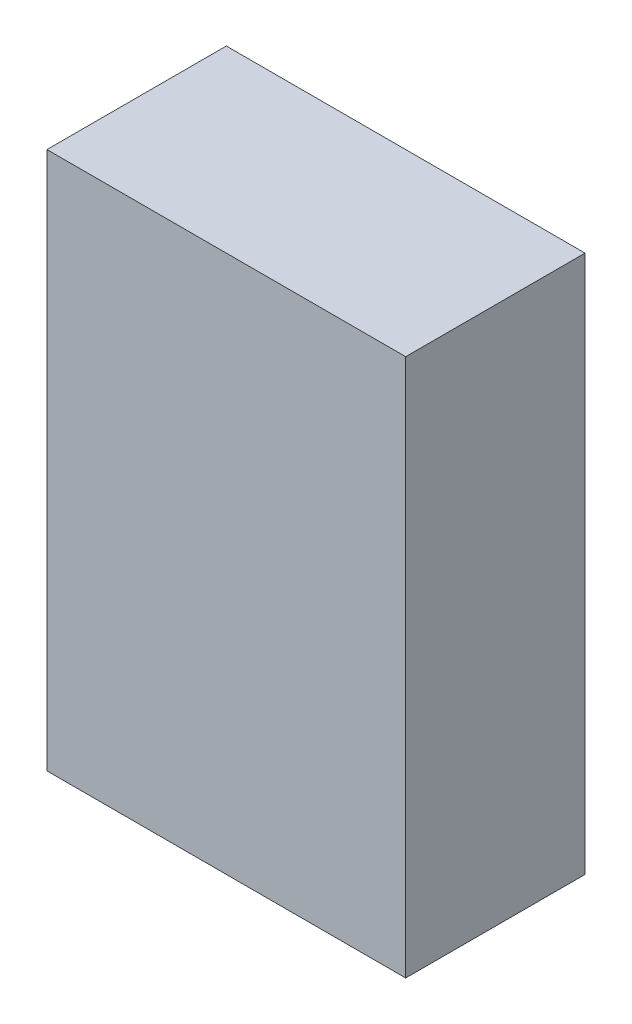
SolidWorks part; units mm, degrees
ref_plane "前视基准面" through (0, 0, 0) normal (0, 0, 1) x (1, 0, 0)
ref_plane "上视基准面" through (0, 0, 0) normal (0, 1, 0) x (1, 0, 0)
ref_plane "右视基准面" through (0, 0, 0) normal (1, 0, 0) x (0, 0, -1)
sketch "草图1" plane through (0, 0, 0) normal (0, 0, 1) x (1, 0, 0)
  line L1 (-1.3841, 28.5244) -> (18.6159, 28.5244)
  line L2 (-1.3841, 28.5244) -> (-1.3841, -1.4756)
  line L3 (-1.3841, -1.4756) -> (18.6159, -1.4756)
  line L4 (18.6159, 28.5244) -> (18.6159, -1.4756)
  dimension "D1" = 30
  dimension "D2" = 20
extrude "凸台-拉伸1" add sketch "草图1" along normal blind 10
